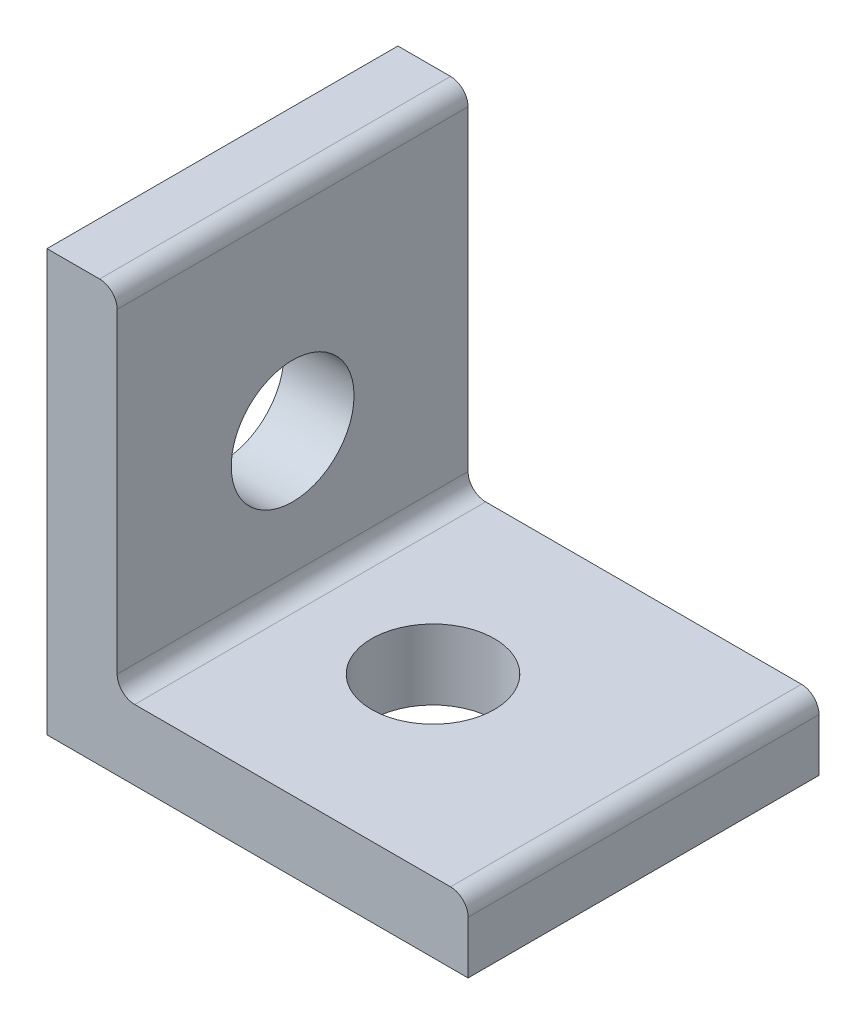
SolidWorks part; units mm, degrees
ref_plane "Front Plane" through (0, 0, 0) normal (0, 0, 1) x (1, 0, 0)
ref_plane "Top Plane" through (0, 0, 0) normal (0, 1, 0) x (1, 0, 0)
ref_plane "Right Plane" through (0, 0, 0) normal (1, 0, 0) x (0, 0, -1)
sketch "Sketch1" plane through (0, 0, 0) normal (0, 0, 1) x (1, 0, 0)
  line L0 (-6, 6) -> (-4, 6)
  line L1 (-4, 6) -> (-4, -4)
  line L2 (-4, -4) -> (6, -4)
  line L3 (6, -4) -> (6, -6)
  line L4 (6, -6) -> (-6, -6)
  line L5 (-6, -6) -> (-6, 6)
  line L6 (0, -6) -> (0, 0) construction
  line L7 (0, 0) -> (-6, 0) construction
  arc A0 (-4.5, 6) -> (-4, 5.5) centre (-4.5, 5.5) cw
  arc A1 (5.5, -4) -> (6, -4.5) centre (5.5, -4.5) cw
  dimension "D4" = 0.5
  dimension "D5" = 0.5
  dimension "D1" = 12
  dimension "D2" = 12
  dimension "D3" = 2
sketch "Sketch2" plane through (0, 0, 0) normal (0, 1, 0) x (1, 0, 0)
  line L0 (0, 0) -> (-6, 0) construction
  line L1 (-6, 5) -> (6, 5)
  line L2 (-6, 5) -> (-6, -5)
  line L3 (-6, -5) -> (6, -5)
  line L4 (6, 5) -> (6, -5)
  line L5 (-6, 0) -> (0, 0) construction
  circle A0 centre (0, 0) radius 1.75
  dimension "D2" = 5
  dimension "D3" = 3.5
  dimension "Thickness/Height/For Rail Height" = 10
  dimension "D4" = 6
sketch "Sketch3" plane through (0, 0, 0) normal (1, 0, 0) x (0, 0, -1)
  line L0 (0, -6) -> (0, 0) construction
  line L1 (-5, 6) -> (5, 6)
  line L2 (-5, 6) -> (-5, -6)
  line L3 (-5, -6) -> (5, -6)
  line L4 (5, 6) -> (5, -6)
  line L5 (0, -6) -> (0, 0) construction
  circle A0 centre (0, 0) radius 1.75
  dimension "D4" = 3.5
  dimension "D1" = 10
  dimension "D2" = 5
  dimension "D3" = 6
sketch "Sketch4" plane through (0, 0, 0) normal (0, 0, 1) x (1, 0, 0)
  line L0 (-6, 6) -> (-6, -6)
  line L1 (-6, -6) -> (6, -6)
  line L2 (6, -6) -> (6, -4.5)
  line L3 (-6, 6) -> (-4.5, 6)
  line L4 (5.5, -4) -> (-3.5, -4)
  line L5 (-4, -3.5) -> (-4, 5.5)
  arc A0 (-4, 5.5) -> (-4.5, 6) centre (-4.5, 5.5) ccw construction
  arc A1 (6, -4.5) -> (5.5, -4) centre (5.5, -4.5) ccw construction
  arc A2 (-4, 5.5) -> (-4.5, 6) centre (-4.5, 5.5) ccw
  arc A3 (6, -4.5) -> (5.5, -4) centre (5.5, -4.5) ccw
  arc A4 (-3.5, -4) -> (-4, -3.5) centre (-3.5, -3.5) cw
  point P17 (-4, -4)
extrude "Boss-Extrude1" add sketch "Sketch4" along normal up to vertex (5 mm away) from vertex at -5 starting at point (0, -6, -5)
sketch "Sketch5" plane through (0, 0, 0) normal (1, 0, 0) x (0, 0, -1)
  circle A0 centre (0, 0) radius 1.75 construction
  circle A1 centre (0, 0) radius 1.75
extrude "Cut-Extrude1" cut sketch "Sketch5" against normal through all
sketch "Sketch6" plane through (0, 0, 0) normal (0, 1, 0) x (1, 0, 0)
  circle A0 centre (0, 0) radius 1.75 construction
  circle A1 centre (0, 0) radius 1.75
extrude "Cut-Extrude2" cut sketch "Sketch6" against normal through all
equation "\"D4@Sketch3\" = \"D3@Sketch2\""
